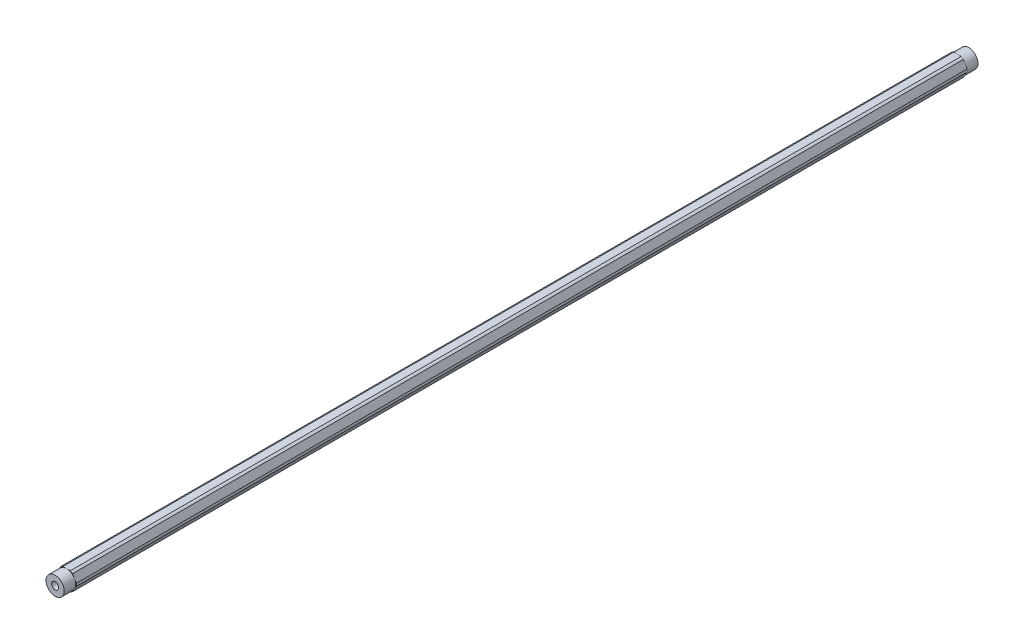
SolidWorks part; units mm, degrees
ref_plane "Front Plane" through (0, 0, 0) normal (0, 0, 1) x (1, 0, 0)
ref_plane "Top Plane" through (0, 0, 0) normal (0, 1, 0) x (1, 0, 0)
ref_plane "Right Plane" through (0, 0, 0) normal (1, 0, 0) x (0, 0, -1)
sketch "Sketch1" plane through (0, 0, 0) normal (0, 0, 1) x (1, 0, 0)
  line L1 (7.3323, 0) -> (3.6662, 6.35)
  line L2 (3.6662, 6.35) -> (-3.6662, 6.35)
  line L3 (-3.6662, 6.35) -> (-7.3323, 0)
  line L4 (-7.3323, 0) -> (-3.6662, -6.35)
  line L5 (-3.6662, -6.35) -> (3.6662, -6.35)
  line L6 (3.6662, -6.35) -> (7.3323, 0)
  circle A0 centre (0, 0) radius 6.35 construction
  dimension "D1" = 12.7
extrude "Boss-Extrude1" add sketch "Sketch1" along normal mid plane 635
sketch "Sketch3" plane through (0, 0, 317.5) normal (0, 0, 1) x (1, 0, 0)
  circle A0 centre (0, 0) radius 6.35
extrude "Cut-Extrude2" cut sketch "Sketch3" against normal blind 7.9502 flip side to cut
mirror "Mirror1" about plane through (0, 0, 0) normal (0, 0, 1) of "Cut-Extrude2"
sketch "Sketch4" plane through (0, 0, 317.5) normal (0, 0, 1) x (1, 0, 0)
  circle A0 centre (0, 0) radius 6.858
  dimension "D1" = 13.716
extrude "Cut-Extrude3" cut sketch "Sketch4" against normal through all flip side to cut
sketch "Sketch5" plane through (0, 0, 317.5) normal (0, 0, 1) x (1, 0, 0)
  circle A0 centre (0, 0) radius 2.4892
  dimension "D1" = 4.9784
extrude "Cut-Extrude4" cut sketch "Sketch5" against normal through all
